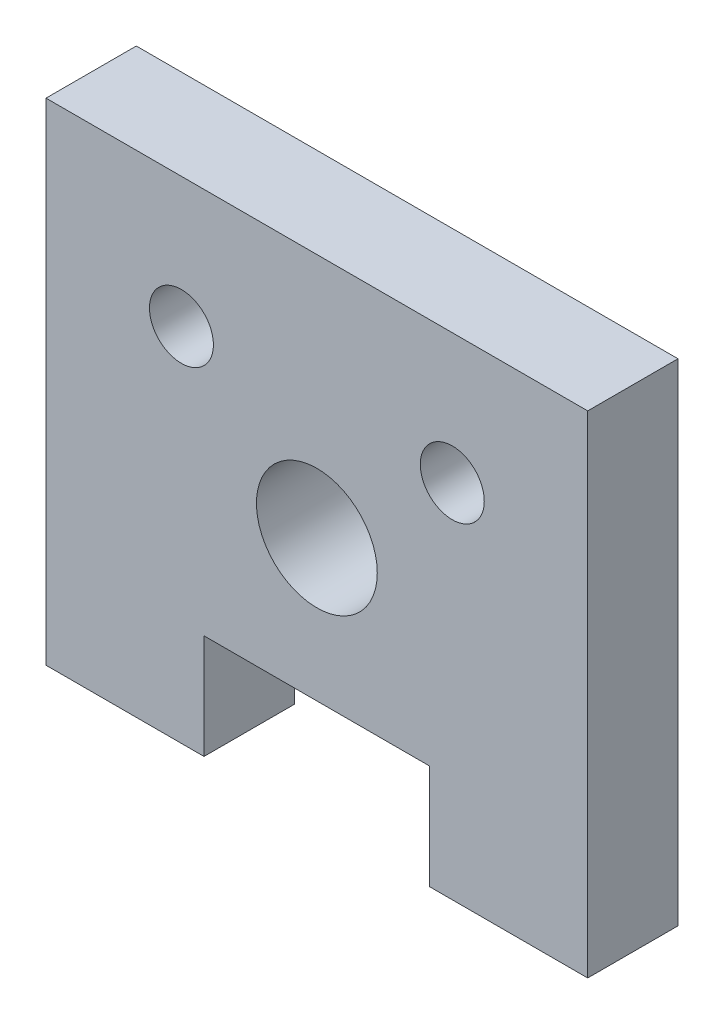
SolidWorks part; units mm, degrees
material "Acrylic (Medium-high impact)"
ref_plane "Front Plane" through (0, 0, 0) normal (0, 0, 1) x (1, 0, 0)
ref_plane "Top Plane" through (0, 0, 0) normal (0, 1, 0) x (1, 0, 0)
ref_plane "Right Plane" through (0, 0, 0) normal (1, 0, 0) x (0, 0, -1)
sketch "Sketch1" plane through (0, 0, 0) normal (0, 0, 1) x (1, 0, 0)
  line L0 (-15.875, -34.544) -> (-15.875, -19.844)
  line L1 (38.1, -34.544) -> (15.875, -34.544)
  line L2 (38.1, -34.544) -> (38.1, 34.544)
  line L3 (38.1, 34.544) -> (-38.1, 34.544)
  line L4 (-38.1, -34.544) -> (-38.1, 34.544)
  line L5 (-15.875, -19.844) -> (15.875, -19.844)
  line L6 (15.875, -19.844) -> (15.875, -34.544)
  line L7 (-15.875, -34.544) -> (-38.1, -34.544)
  circle A0 centre (0, 0) radius 8.5
  circle A1 centre (19.05, 16.256) radius 4.5
  circle A2 centre (-19.05, 16.256) radius 4.5
  point P0 (0, 0)
  point P6 (-38.1, 0)
  point P7 (0, 34.544)
  dimension "D3" = 17
  dimension "D4" = 9
  dimension "D1" = 76.2
  dimension "D2" = 69.088
  dimension "D5" = 19.05
  dimension "D6" = 50.8
  dimension "D7" = 19.05
  dimension "D8" = 31.75
  dimension "D9" = 14.7
extrude "Boss-Extrude1" add sketch "Sketch1" along normal blind 12.7
